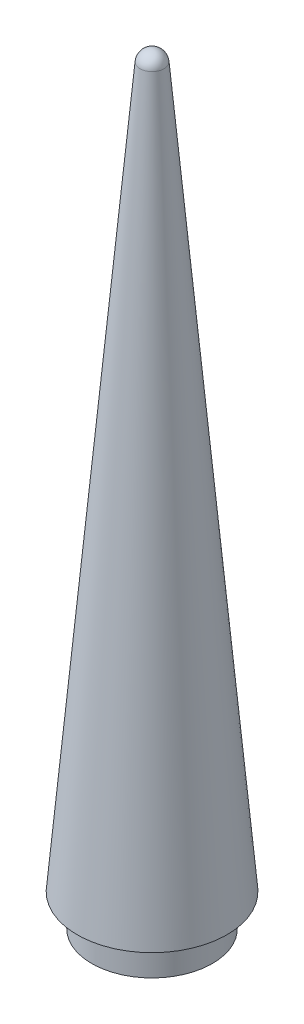
SolidWorks part; units mm, degrees
material "6061 Alloy"
ref_plane "Front Plane" through (0, 0, 0) normal (0, 0, 1) x (1, 0, 0)
ref_plane "Top Plane" through (0, 0, 0) normal (0, 1, 0) x (1, 0, 0)
ref_plane "Right Plane" through (0, 0, 0) normal (1, 0, 0) x (0, 0, -1)
sketch "Sketch2" plane through (0, 0, 0) normal (0, 0, 1) x (1, 0, 0)
  line L0 (0, 6.473) -> (0, 141.5732)
  line L1 (0, 141.5732) -> (11.8197, 6.473)
  line L2 (11.8197, 6.473) -> (9.525, 6.473)
  line L3 (9.525, 6.473) -> (9.525, 1.393)
  line L4 (9.525, 1.393) -> (0, 1.393)
  line L5 (0, 1.393) -> (0, 6.473)
  line L6 (0, 121.6208) -> (-2.1023, 121.6208) construction
  line L7 (0, -200166.8953) -> (0, 200141.5732) construction
  line L8 (11.8197, 6.473) -> (-11.8197, 6.473) construction
  line L9 (0, 141.5732) -> (26.9875, -166.8953) construction
  arc A0 (1.8978, 119.8818) -> (0, 121.6208) centre (0, 119.7158) ccw
revolve "Revolve1" add sketch "Sketch2" angle 360 about L0
sketch "Sketch3" plane through (0, 1.393, 0) normal (0, -1, 0) x (1, 0, 0)
  point P0 (0, 0)
hole_wizard "1/4-20 Tapped Hole1" positions "Sketch3" profile "Sketch4" tap size "1/4-20" standard "ANSI Inch"
sketch "Sketch4" plane through (0, 1.393, 0) normal (1, 0, 0) x (0, 0, -1)
  line L0 (0, 0) -> (0, 65.0338)
  line L1 (0, 65.0338) -> (2.5527, 63.5)
  line L2 (2.5527, 63.5) -> (2.5527, 1.2573)
  line L3 (2.5527, 1.2573) -> (3.81, 0)
  line L5 (3.81, 0) -> (0, 0)
  line L6 (-2.5527, 1.2573) -> (-3.81, 0) construction
  line L10 (0, 65.0338) -> (-2.5527, 63.5) construction
  line L11 (0, -6.35) -> (0, 107.95) construction
  dimension "Tap Drill Dia." = 5.1054
  dimension "Tap Drill Depth" = 63.5
  dimension "Near C'Sink Dia." = 7.62
  dimension "Near C'Sink Angle" = 90
  dimension "Drill Angle" = 118
cosmetic thread "Hole Thread1" parameters "D1"=50.8, "D2"=6.35
